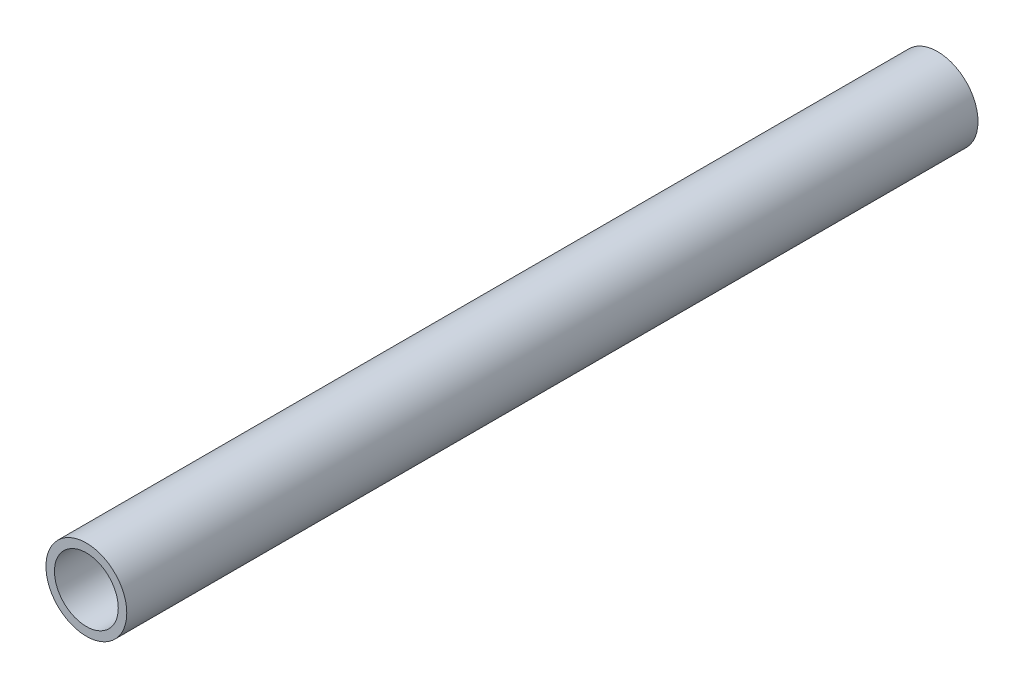
SolidWorks part; units mm, degrees
ref_plane "Front Plane" through (0, 0, 0) normal (0, 0, 1) x (1, 0, 0)
ref_plane "Top Plane" through (0, 0, 0) normal (0, 1, 0) x (1, 0, 0)
ref_plane "Right Plane" through (0, 0, 0) normal (1, 0, 0) x (0, 0, -1)
sketch "Sketch1" plane through (0, 0, 0) normal (0, 0, 1) x (1, 0, 0)
  circle A0 centre (0, 0) radius 9.5
  circle A1 centre (0, 0) radius 7.5
  dimension "D1" = 15
  dimension "D2" = 19
extrude "Boss-Extrude1" add sketch "Sketch1" along normal blind 200
